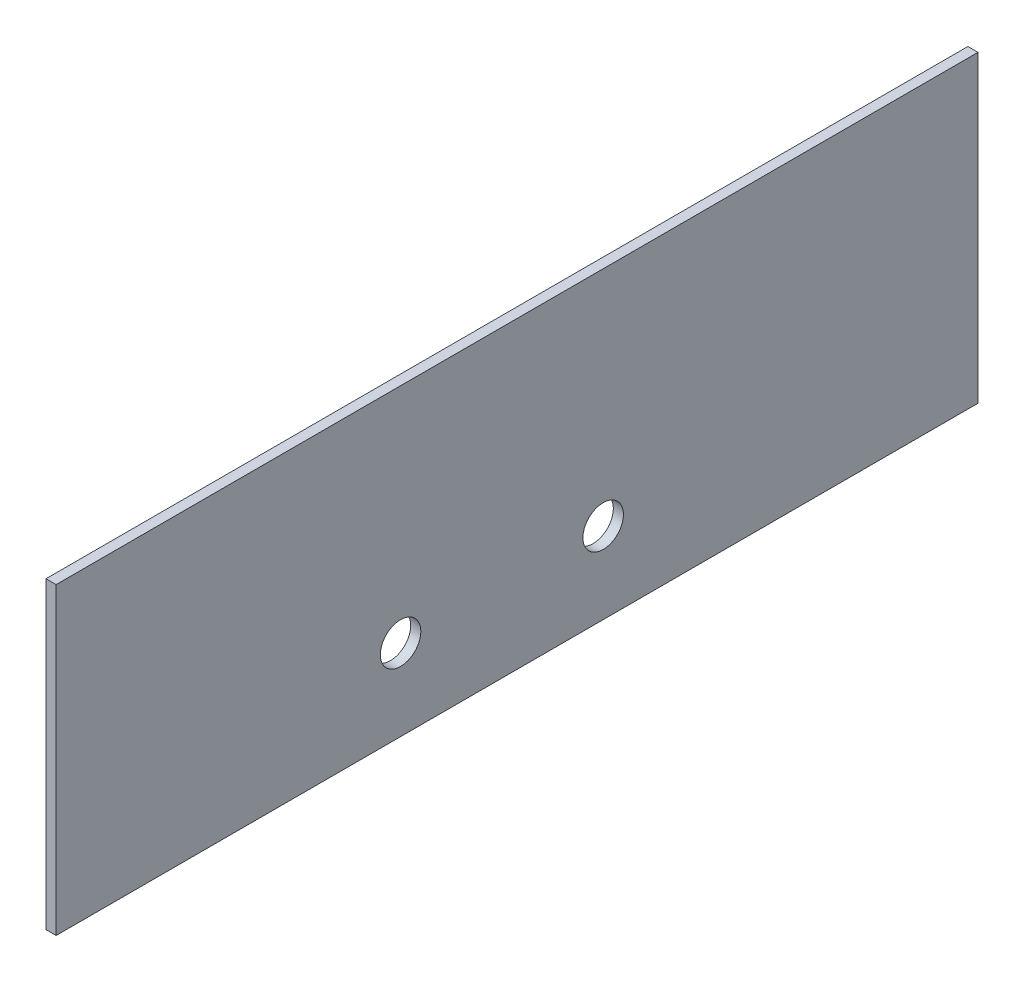
SolidWorks part; units mm, degrees
ref_plane "Front Plane" through (0, 0, 0) normal (0, 0, 1) x (1, 0, 0)
ref_plane "Top Plane" through (0, 0, 0) normal (0, 1, 0) x (1, 0, 0)
ref_plane "Right Plane" through (0, 0, 0) normal (1, 0, 0) x (0, 0, -1)
sketch "Sketch2" plane through (-60, 0, 0) normal (-1, 0, 0) x (0, 0, 1)
  line L1 (-2, 60) -> (180, 60)
  line L2 (-2, 60) -> (-2, 0)
  line L3 (-2, 0) -> (180, 0)
  line L4 (180, 60) -> (180, 0)
extrude "Boss-Extrude1" add sketch "Sketch2" along normal blind 2 contours L4 L3 L2 L1
hole_wizard "Ø8.0mm Dowel Hole2" positions "Sketch5" profile "Sketch6" hole size "Ø8.0" standard "BSI" end condition up to next
sketch "Sketch5" plane through (-62, 0, 0) normal (-1, 0, 0) x (0, 0, 1)
  line L0 (-2, 0) -> (180, 0) construction
  line L1 (180, 60) -> (180, 0) construction
  point P0 (112, 16)
  point P2 (72, 16)
  dimension "D1" = 16
  dimension "D2" = 40
  dimension "D3" = 68
sketch "Sketch6" plane through (-62, 16, 112) normal (0, 1, 0) x (0, 0, 1)
  line L0 (0, 0) -> (0, 2)
  line L1 (0, 2) -> (4, 2)
  line L2 (4, 2) -> (4, 0)
  line L5 (4, 0) -> (0, 0)
  line L11 (0, -6.35) -> (0, 107.95) construction
  dimension "Thru Hole Dia." = 8
  dimension "Thru Hole Depth" = 2
